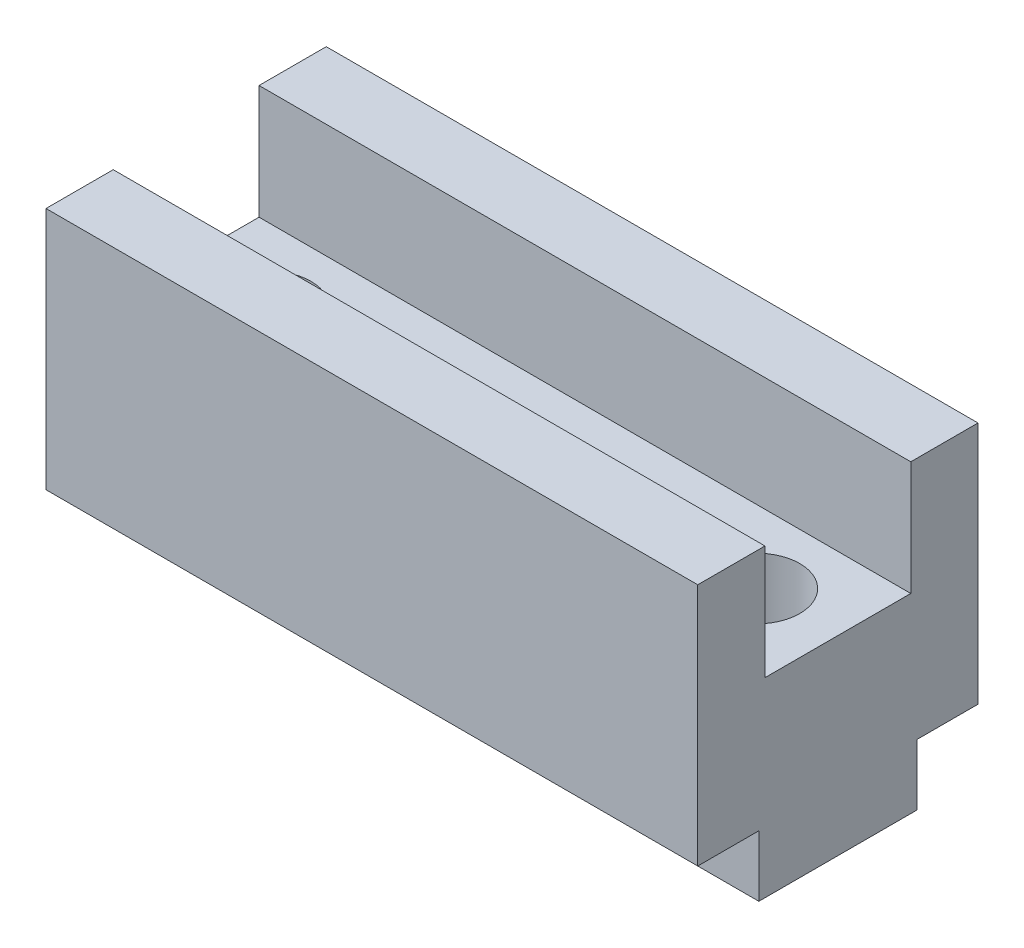
SolidWorks part; units mm, degrees
material "AISI 304"
ref_plane "Front Plane" through (0, 0, 0) normal (0, 0, 1) x (1, 0, 0)
ref_plane "Top Plane" through (0, 0, 0) normal (0, 1, 0) x (1, 0, 0)
ref_plane "Right Plane" through (0, 0, 0) normal (1, 0, 0) x (0, 0, -1)
sketch "Sketch1" plane through (0, 0, 0) normal (0, 1, 0) x (1, 0, 0)
  line L1 (-25.4, -10.922) -> (25.4, -10.922)
  line L2 (-25.4, -10.922) -> (-25.4, 10.922)
  line L3 (-25.4, 10.922) -> (25.4, 10.922)
  line L4 (25.4, -10.922) -> (25.4, 10.922)
  line L5 (-25.4, -10.922) -> (25.4, 10.922) construction
  line L6 (-25.4, 10.922) -> (25.4, -10.922) construction
  point P0 (0, 0)
  dimension "D1" = 50.8
  dimension "D2" = 21.844
extrude "Stock" add sketch "Sketch1" along normal blind 23.749
sketch "Bolt Hole Pattern" plane through (0, 23.749, 0) normal (0, 1, 0) x (1, 0, 0)
  point P0 (19.05, 0)
  point P1 (-19.05, 0)
  dimension "D1" = 19.05
  dimension "D2" = 19.05
hole_wizard "Clearance holes for Mounting Bolts " positions "Sketch4" profile "Sketch3" hole size "1/4" standard "ANSI Inch" end condition up to next
sketch "Sketch4" plane through (0, 23.749, 0) normal (0, 1, 0) x (1, 0, 0)
  point P0 (-19.05, 0)
  point P3 (19.05, 0)
sketch "Sketch3" plane through (-19.05, 23.749, 0) normal (1, 0, 0) x (0, 0, 1)
  line L0 (0, 0) -> (0, 23.749)
  line L1 (0, 23.749) -> (3.3782, 23.749)
  line L2 (3.3782, 23.749) -> (3.3782, 0)
  line L5 (3.3782, 0) -> (0, 0)
  line L11 (0, -6.35) -> (0, 107.95) construction
  dimension "Thru Hole Dia." = 6.7564
  dimension "Thru Hole Depth" = 23.749
sketch "Sketch5" plane through (0, 0, 0) normal (0, -1, 0) x (1, 0, 0)
  line L0 (25.4, 10.922) -> (25.4, -10.922) construction
  line L1 (-25.4, 10.922) -> (25.4, 10.922)
  line L2 (-25.4, 10.922) -> (-25.4, 6.1595)
  line L3 (-25.4, 6.1595) -> (25.4, 6.1595)
  line L4 (25.4, 10.922) -> (25.4, 6.1595)
  line L5 (-25.4, 0) -> (25.4, 0) construction
  line L6 (-25.4, -10.922) -> (-25.4, 10.922) construction
  line L7 (25.4, -10.922) -> (25.4, -6.1595)
  line L8 (-25.4, -6.1595) -> (25.4, -6.1595)
  line L9 (-25.4, -10.922) -> (-25.4, -6.1595)
  line L10 (-25.4, -10.922) -> (25.4, -10.922)
  dimension "D1" = 4.7625
extrude "Clearance Rabbit" cut sketch "Sketch5" against normal blind 4.7625
sketch "Sketch6" plane through (25.4, 0, 0) normal (1, 0, 0) x (0, 0, -1)
  line L0 (-10.922, 23.749) -> (10.922, 23.749) construction
  line L1 (-5.6832, 32.639) -> (5.6833, 32.639)
  line L2 (-5.6832, 32.639) -> (-5.6832, 14.859)
  line L3 (-5.6832, 14.859) -> (5.6833, 14.859)
  line L4 (5.6833, 32.639) -> (5.6833, 14.859)
  line L5 (-5.6832, 32.639) -> (5.6833, 14.859) construction
  line L6 (-5.6832, 14.859) -> (5.6833, 32.639) construction
  point P0 (0, 23.749)
  dimension "D1" = 11.3665
  dimension "D2" = 8.89
extrude "Nut Slot" cut sketch "Sketch6" against normal through all
